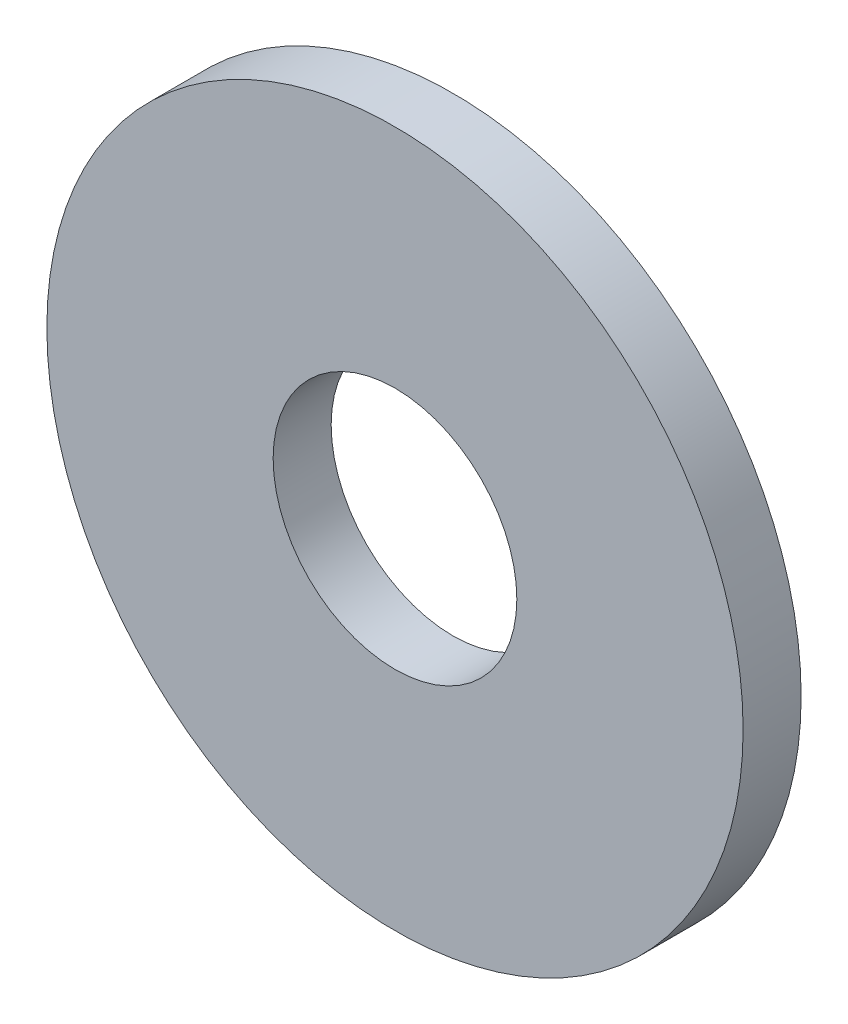
SolidWorks part; units mm, degrees
material "Cast Stainless Steel"
ref_plane "Front Plane" through (0, 0, 0) normal (0, 0, 1) x (1, 0, 0)
ref_plane "Top Plane" through (0, 0, 0) normal (0, 1, 0) x (1, 0, 0)
ref_plane "Right Plane" through (0, 0, 0) normal (1, 0, 0) x (0, 0, -1)
sketch "Sketch1" plane through (0, 0, 0) normal (0, 0, 1) x (1, 0, 0)
  circle A0 centre (0, 0) radius 12
  circle A1 centre (0, 0) radius 4.2
  dimension "OD" = 24
  dimension "ID1" = 8.4
extrude "Boss-Extrude1" add sketch "Sketch1" along normal blind 2
